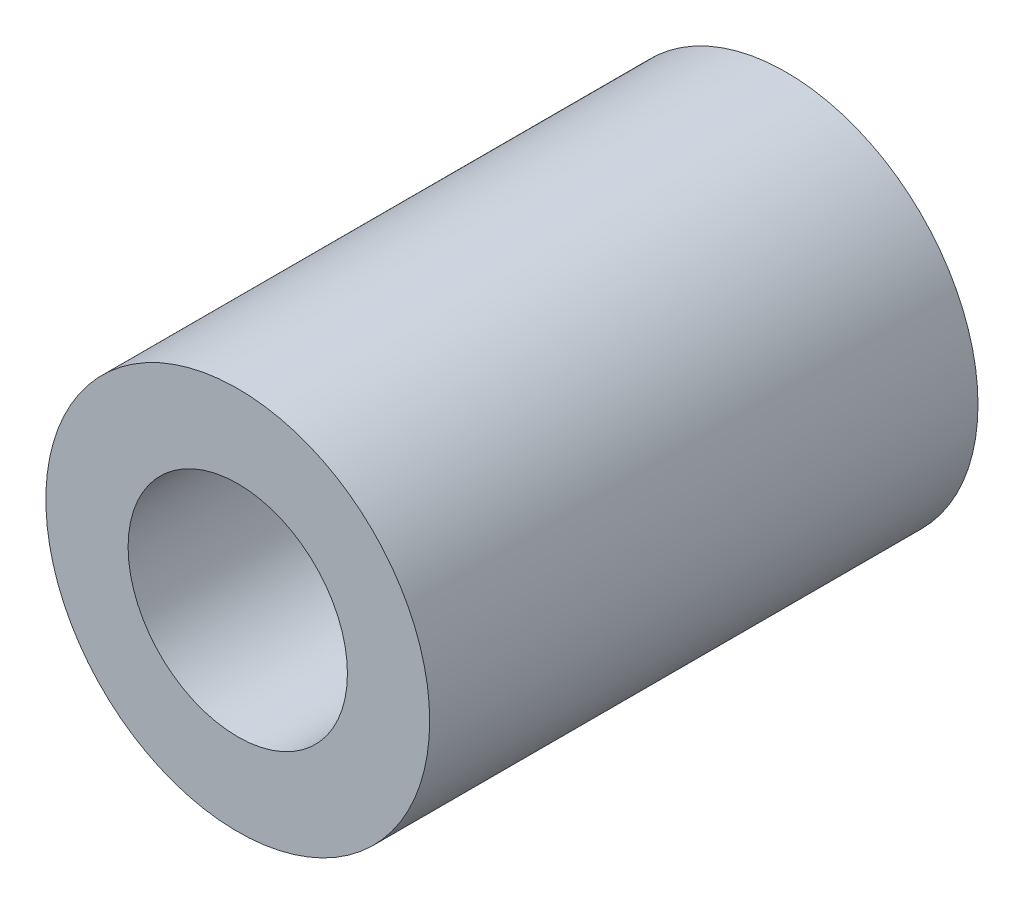
SolidWorks part; units mm, degrees
ref_plane "前视基准面" through (0, 0, 0) normal (0, 0, 1) x (1, 0, 0)
ref_plane "上视基准面" through (0, 0, 0) normal (0, 1, 0) x (1, 0, 0)
ref_plane "右视基准面" through (0, 0, 0) normal (1, 0, 0) x (0, 0, -1)
sketch "草图1" plane through (0, 0, 0) normal (0, 0, 1) x (1, 0, 0)
  circle A0 centre (0, 0) radius 3.5
  circle A1 centre (0, 0) radius 2
  dimension "D1" = 7
  dimension "D2" = 4
extrude "凸台-拉伸1" add sketch "草图1" along normal blind 10
